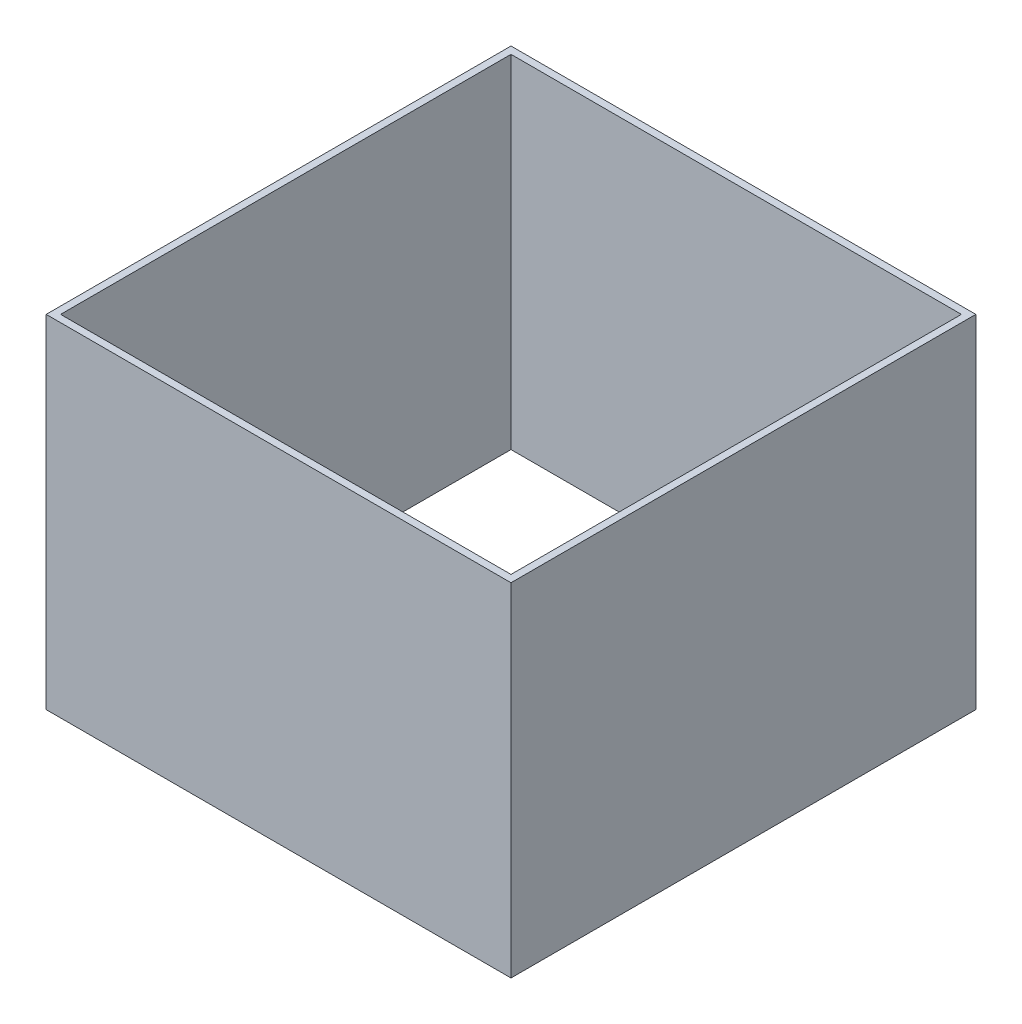
SolidWorks part; units mm, degrees
ref_plane "Front Plane" through (0, 0, 0) normal (0, 0, 1) x (1, 0, 0)
ref_plane "Top Plane" through (0, 0, 0) normal (0, 1, 0) x (1, 0, 0)
ref_plane "Right Plane" through (0, 0, 0) normal (1, 0, 0) x (0, 0, -1)
sketch "Sketch1" plane through (0, 0, 0) normal (0, 1, 0) x (1, 0, 0)
  line L1 (-125, 125) -> (125, 125)
  line L2 (-125, 125) -> (-125, -125)
  line L3 (-125, -125) -> (125, -125)
  line L4 (125, 125) -> (125, -125)
  line L5 (-125, 125) -> (125, -125) construction
  line L6 (-125, -125) -> (125, 125) construction
  line L7 (-129, 129) -> (129, 129)
  line L8 (-129, 129) -> (-129, -129)
  line L9 (-129, -129) -> (129, -129)
  line L10 (129, 129) -> (129, -129)
  line L11 (-129, 129) -> (129, -129) construction
  line L12 (-129, -129) -> (129, 129) construction
  point P0 (0, 0)
  point P5 (0, 0)
  point P7 (0, 0)
  dimension "D1" = 250
  dimension "D2" = 250
  dimension "D3" = 4
  dimension "D4" = 4
extrude "Boss-Extrude1" add sketch "Sketch1" along normal blind 190
